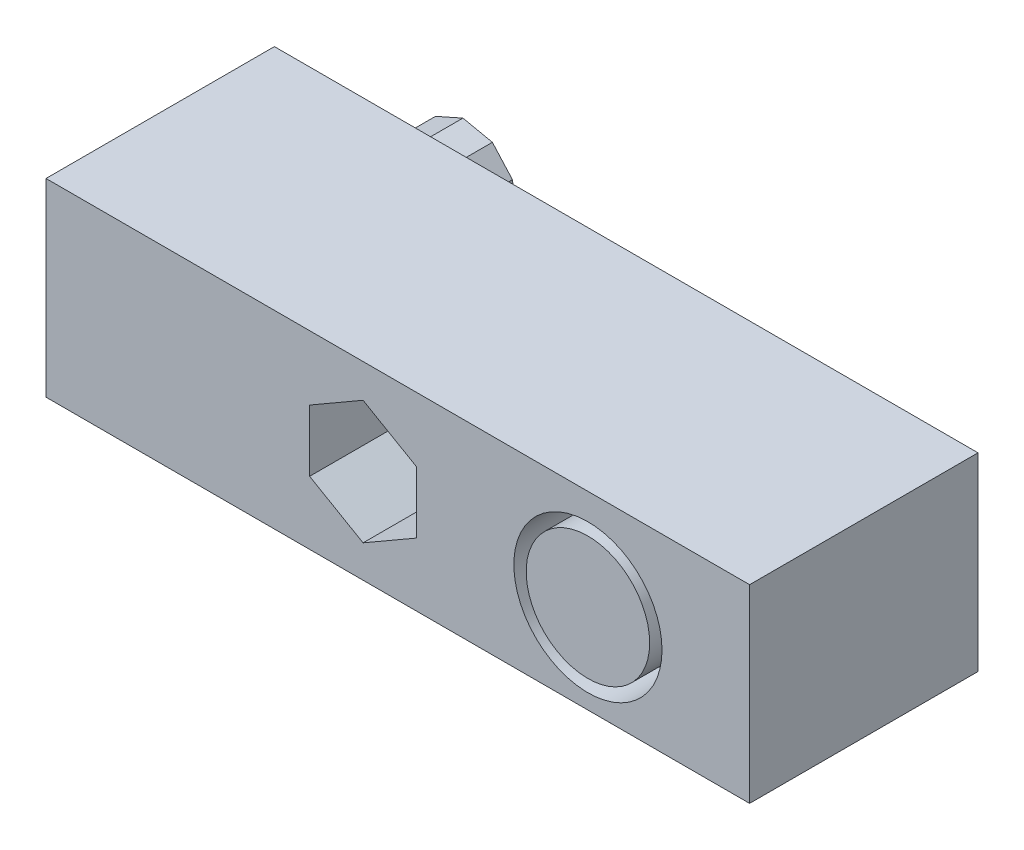
SolidWorks part; units mm, degrees
ref_plane "Front Plane" through (0, 0, 0) normal (0, 0, 1) x (1, 0, 0)
ref_plane "Top Plane" through (0, 0, 0) normal (0, 1, 0) x (1, 0, 0)
ref_plane "Right Plane" through (0, 0, 0) normal (1, 0, 0) x (0, 0, -1)
sketch "Sketch1" plane through (0, 0, 0) normal (0, 0, 1) x (1, 0, 0)
  line L1 (-51.3648, 12.6033) -> (62.6128, 12.6033)
  line L2 (-51.3648, 12.6033) -> (-51.3648, -18.083)
  line L3 (-51.3648, -18.083) -> (62.6128, -18.083)
  line L4 (62.6128, 12.6033) -> (62.6128, -18.083)
extrude "Boss-Extrude1" add sketch "Sketch1" along normal blind 37
sketch "Sketch2" plane through (0, 0, 37) normal (0, 0, 1) x (1, 0, 0)
  line L1 (-8.6603, -7.8328) -> (0, -12.8328)
  line L2 (0, -12.8328) -> (8.6603, -7.8328)
  line L3 (8.6603, -7.8328) -> (8.6603, 2.1672)
  line L4 (8.6603, 2.1672) -> (0, 7.1672)
  line L5 (0, 7.1672) -> (-8.6603, 2.1672)
  line L6 (-8.6603, 2.1672) -> (-8.6603, -7.8328)
  circle A0 centre (0, -2.8328) radius 8.6603 construction
  dimension "D1" = 10
extrude "Cut-Extrude1" cut sketch "Sketch2" against normal blind 37
sketch "Sketch3" plane through (0, 0, 37) normal (0, 0, 1) x (1, 0, 0)
  circle A0 centre (36.4253, -3.6579) radius 9.9996
  circle A1 centre (36.4253, -3.6579) radius 12
extrude "Cut-Extrude2" cut sketch "Sketch3" against normal blind 37
sketch "Sketch4" plane through (0, 0, 0) normal (0, 0, -1) x (-1, 0, 0)
  line L0 (22.7958, 3.2075) -> (22.2864, -1.6396)
  line L1 (24.3667, 3.3574) -> (24.2758, -3.1999)
  line L2 (24.2758, -3.1999) -> (29.9091, -6.5573)
  line L3 (29.9091, -6.5573) -> (35.6333, -3.3574)
  line L4 (35.6333, -3.3574) -> (35.7242, 3.1999)
  line L5 (35.7242, 3.1999) -> (30.0909, 6.5573)
  line L6 (30.0909, 6.5573) -> (24.3667, 3.3574)
  line L7 (33.943, -6.8294) -> (37.2042, -3.2075)
  line L8 (37.2042, -3.2075) -> (37.7136, 1.6396)
  line L9 (37.7136, 1.6396) -> (35.2767, 5.8604)
  line L10 (35.2767, 5.8604) -> (30.8243, 7.8428)
  line L11 (30.8243, 7.8428) -> (26.057, 6.8294)
  line L12 (26.057, 6.8294) -> (22.7958, 3.2075)
  line L13 (22.2864, -1.6396) -> (24.7233, -5.8604)
  line L14 (24.7233, -5.8604) -> (29.1757, -7.8428)
  line L15 (29.1757, -7.8428) -> (33.943, -6.8294)
  circle A0 centre (30, 0) radius 5.6793 construction
  circle A1 centre (30, 0) radius 7.5 construction
extrude "Boss-Extrude2" add sketch "Sketch4" along normal blind 10
